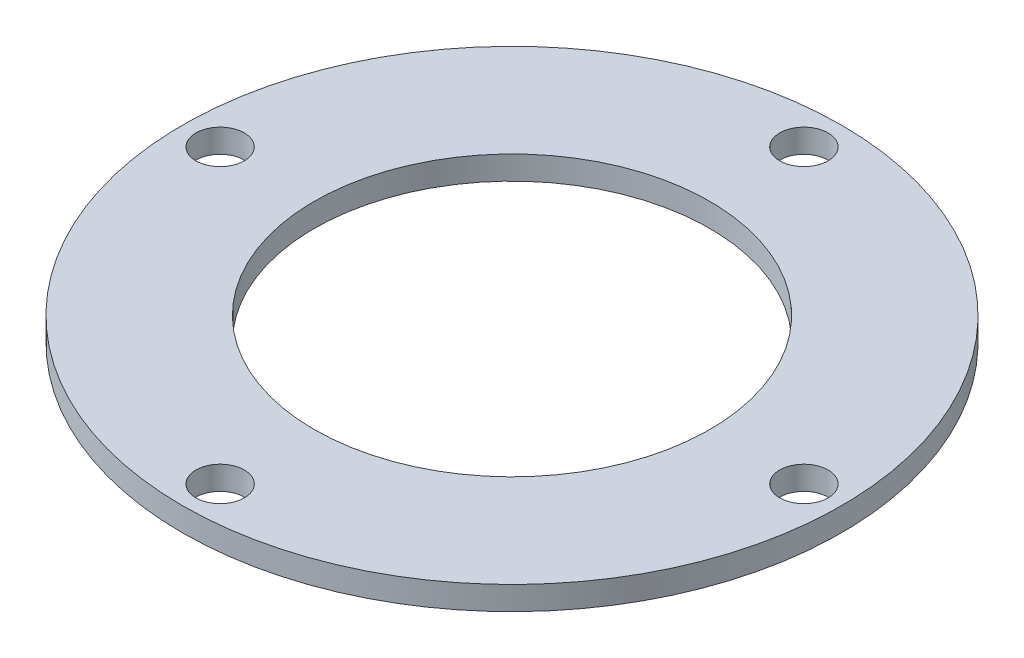
SolidWorks part; units mm, degrees
material "Brass"
ref_plane "Front Plane" through (0, 0, 0) normal (0, 0, 1) x (1, 0, 0)
ref_plane "Top Plane" through (0, 0, 0) normal (0, 1, 0) x (1, 0, 0)
ref_plane "Right Plane" through (0, 0, 0) normal (1, 0, 0) x (0, 0, -1)
sketch "Sketch1" plane through (0, 0, 0) normal (0, 1, 0) x (1, 0, 0)
  circle A0 centre (0, 0) radius 44.45
  circle A1 centre (0, 0) radius 26.67
  circle A2 centre (0, 39.37) radius 3.2639
  circle A3 centre (39.37, 0) radius 3.2639
  circle A4 centre (0, -39.37) radius 3.2639
  circle A5 centre (-39.37, 0) radius 3.2639
  point P15 (0, 0)
  dimension "D1" = 88.9
  dimension "D2" = 53.34
  dimension "D4" = 6.5278
  dimension "D3" = 39.37
  dimension "D5" = 4
extrude "Boss-Extrude1" add sketch "Sketch1" along normal blind 3.175
